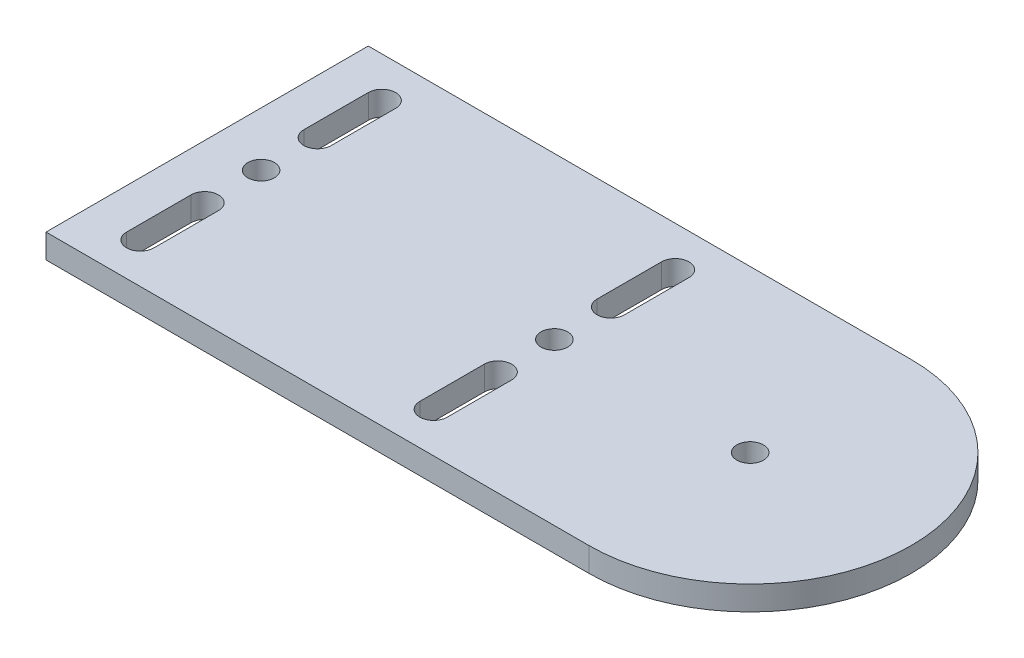
SolidWorks part; units mm, degrees
material "Thornel Mat VMA"
ref_plane "前视基准面" through (0, 0, 0) normal (0, 0, 1) x (1, 0, 0)
ref_plane "上视基准面" through (0, 0, 0) normal (0, 1, 0) x (1, 0, 0)
ref_plane "右视基准面" through (0, 0, 0) normal (1, 0, 0) x (0, 0, -1)
sketch "草图1" plane through (0, 0, 0) normal (0, 1, 0) x (1, 0, 0)
  line L0 (0, 0) -> (85, 0) construction
  line L1 (0, 20) -> (85, 20)
  line L2 (0, -20) -> (85, -20)
  line L3 (42.5, 20) -> (42.5, -20) construction
  line L4 (24.3, 15) -> (24.3, 7) construction
  line L5 (26, 15) -> (26, 7)
  line L6 (22.6, 15) -> (22.6, 7)
  line L7 (24.3, -7) -> (24.3, -15) construction
  line L8 (26, -7) -> (26, -15)
  line L9 (22.6, -7) -> (22.6, -15)
  line L10 (60.7, -7) -> (60.7, -15) construction
  line L11 (59, -7) -> (59, -15)
  line L12 (62.4, -7) -> (62.4, -15)
  line L13 (60.7, 15) -> (60.7, 7) construction
  line L14 (59, 15) -> (59, 7)
  line L15 (62.4, 15) -> (62.4, 7)
  arc A0 (0, 20) -> (0, -20) centre (0, 0) ccw
  arc A1 (85, -20) -> (85, 20) centre (85, 0) ccw
  circle A2 centre (0, 0) radius 1.65
  arc A3 (26, 15) -> (22.6, 15) centre (24.3, 15) ccw
  arc A4 (22.6, 7) -> (26, 7) centre (24.3, 7) ccw
  arc A5 (26, -7) -> (22.6, -7) centre (24.3, -7) ccw
  arc A6 (22.6, -15) -> (26, -15) centre (24.3, -15) ccw
  arc A7 (59, -7) -> (62.4, -7) centre (60.7, -7) cw
  arc A8 (62.4, -15) -> (59, -15) centre (60.7, -15) cw
  arc A9 (59, 15) -> (62.4, 15) centre (60.7, 15) cw
  arc A10 (62.4, 7) -> (59, 7) centre (60.7, 7) cw
  circle A11 centre (85, 0) radius 1.65
  point P3 (42.5, 0)
  point P14 (24.3, 11)
  point P21 (24.3, -11)
  point P26 (26, -11)
  point P30 (60.7, -11)
  point P37 (60.7, 11)
  dimension "D3" = 3.3
  dimension "D11" = 3.3
  dimension "D1" = 85
  dimension "D2" = 40
  dimension "D4" = 8
  dimension "D5" = 3.4
  dimension "D6" = 33
  dimension "D7" = 14
  dimension "D8" = 8
  dimension "D9" = 3.4
  dimension "D10" = 14
extrude "凸台-拉伸1" add sketch "草图1" along normal blind 3
sketch "草图2" plane through (0, 3, 0) normal (0, 1, 0) x (1, 0, 0)
  line L0 (85, 0) -> (0, 0) construction
  line L1 (24.3, 15) -> (24.3, -15) construction
  line L2 (60.7, -15) -> (60.7, 15) construction
  circle A0 centre (24.3, 0) radius 1.65
  circle A1 centre (60.7, 0) radius 1.65
  dimension "D1" = 3.3
  dimension "D2" = 3.3
extrude "切除-拉伸1" cut sketch "草图2" against normal blind 10
sketch "草图3" plane through (0, 0, 0) normal (0, -1, 0) x (1, 0, 0)
  line L0 (17.6, -20) -> (-23.8857, -20)
  line L1 (85, -20) -> (0, -20) construction
  line L2 (-23.8857, -20) -> (-23.8857, 20)
  line L3 (-23.8857, 20) -> (17.6, 20)
  line L4 (0, 20) -> (85, 20) construction
  line L5 (17.6, 20) -> (17.6, -20)
  line L6 (22.6, -15) -> (22.6, -7) construction
  dimension "D1" = 5
extrude "切除-拉伸2" cut sketch "草图3" against normal blind 10
